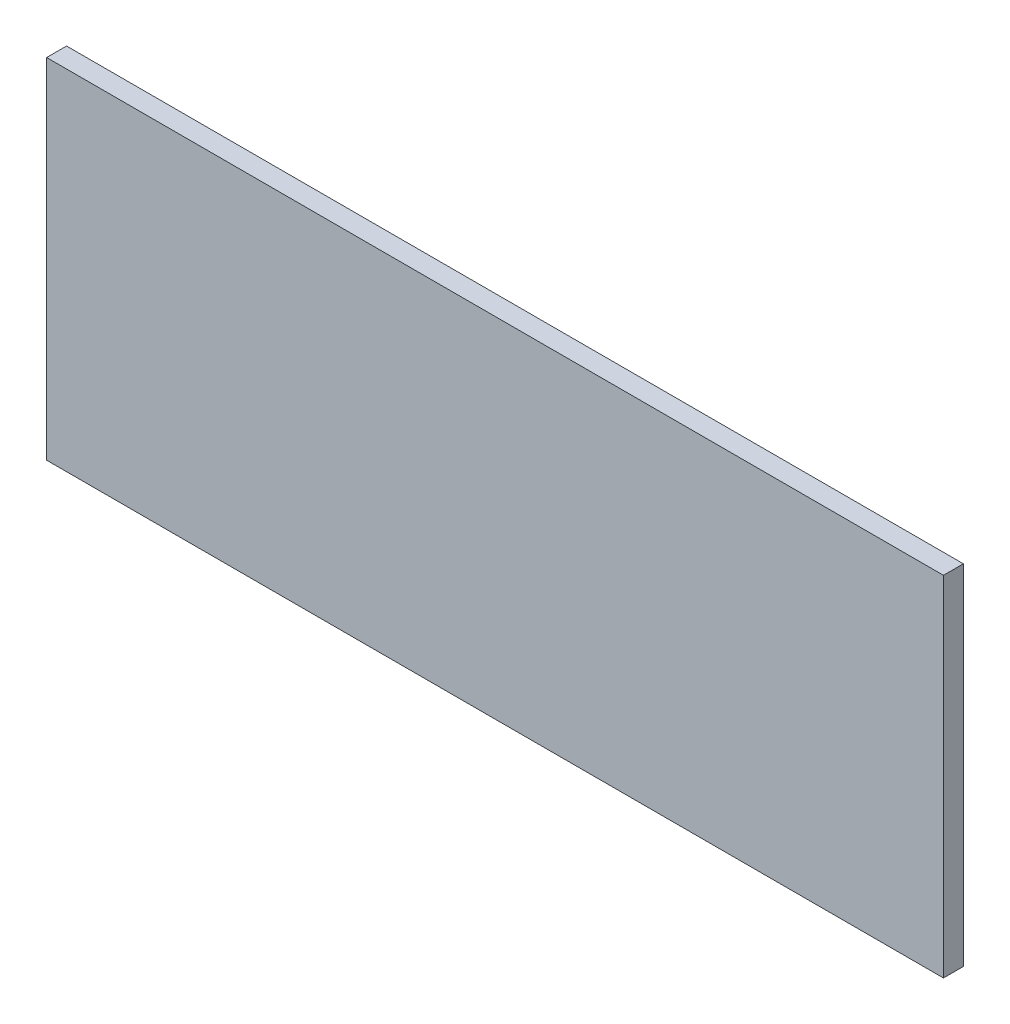
SolidWorks part; units mm, degrees
ref_plane "Front Plane" through (0, 0, 0) normal (0, 0, 1) x (1, 0, 0)
ref_plane "Top Plane" through (0, 0, 0) normal (0, 1, 0) x (1, 0, 0)
ref_plane "Right Plane" through (0, 0, 0) normal (1, 0, 0) x (0, 0, -1)
sketch "Sketch1" plane through (0, 0, 0) normal (0, 0, 1) x (1, 0, 0)
  line L1 (-90, 35) -> (90, 35)
  line L2 (-90, 35) -> (-90, -35)
  line L3 (-90, -35) -> (90, -35)
  line L4 (90, 35) -> (90, -35)
  line L5 (-90, 35) -> (90, -35) construction
  line L6 (-90, -35) -> (90, 35) construction
  point P0 (0, 0)
  dimension "D1" = 180
  dimension "D2" = 70
extrude "Boss-Extrude1" add sketch "Sketch1" along normal blind 4
